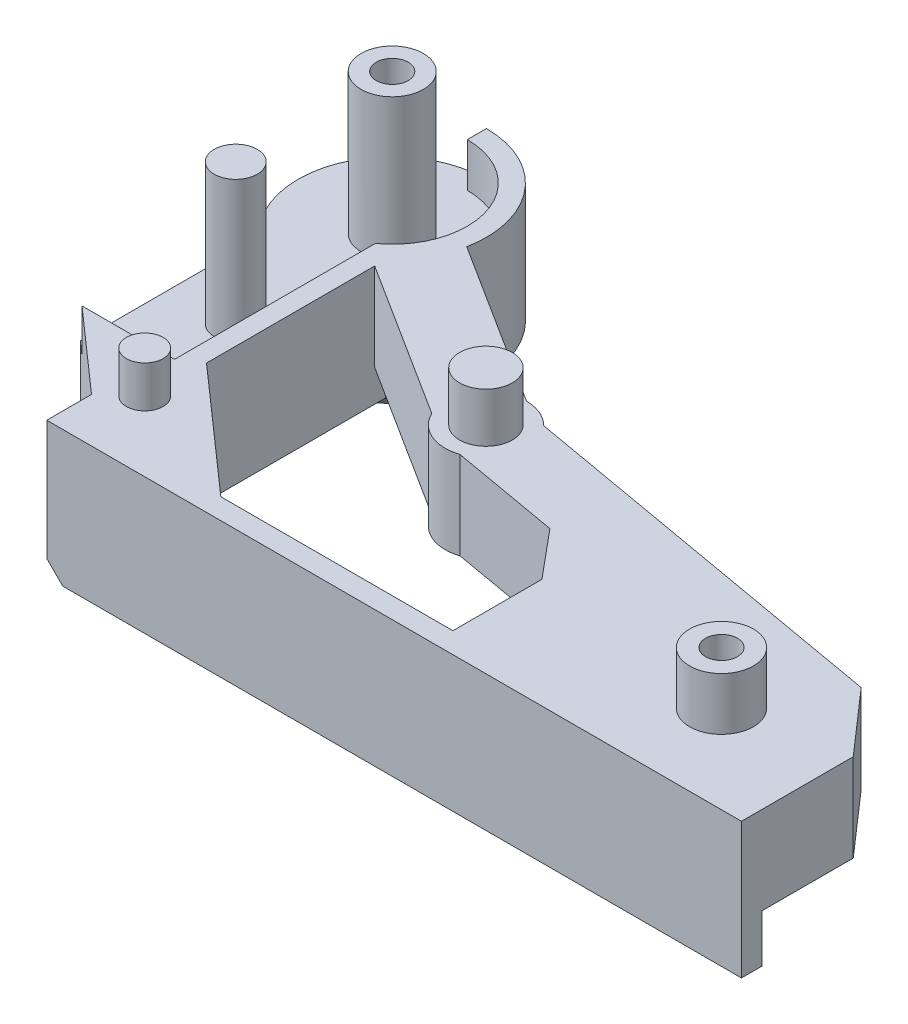
SolidWorks part; units mm, degrees
ref_plane "Front Plane" through (0, 0, 0) normal (0, 0, 1) x (1, 0, 0)
ref_plane "Top Plane" through (0, 0, 0) normal (0, 1, 0) x (1, 0, 0)
ref_plane "Right Plane" through (0, 0, 0) normal (1, 0, 0) x (0, 0, -1)
sketch "Sketch1" plane through (0, 0, 0) normal (0, 1, 0) x (1, 0, 0)
  line L0 (21.75, 0) -> (-21.75, 0)
  line L1 (-21.75, 0) -> (-21.75, 1.3)
  line L2 (-21.75, 1.3) -> (21.75, 1.3)
  line L3 (21.75, 1.3) -> (21.75, 0)
  line L4 (21.75, 0) -> (21.75, 7)
  line L5 (21.75, 7) -> (18.25, 11)
  line L6 (18.25, 11) -> (-7.25, 15.5)
  line L7 (-7.9973, 11.2654) -> (-0.119, 9.8751)
  line L8 (-7.25, 15.5) -> (-7.9973, 11.2654)
  line L9 (-0.119, 9.8751) -> (2.381, 6.8751)
  line L10 (2.381, 6.8751) -> (2.381, 1.3)
  line L11 (-8.9018, 11.6845) -> (-6.5982, 15.3155)
  line L12 (-6.5982, 15.3155) -> (-21.7974, 24.9583)
  line L13 (-21.7974, 24.9583) -> (-24.101, 21.3274)
  line L14 (-24.101, 21.3274) -> (-8.9018, 11.6845)
  line L15 (-7.75, 13.5) -> (-23.8, 23.6826) construction
  line L16 (-21.75, 0) -> (-21.75, 2.8)
  line L17 (-21.75, 2.8) -> (-27.75, 8.1)
  line L18 (-27.75, 8.1) -> (-27.75, 19.3)
  line L19 (-27.75, 19.3) -> (-19.85, 19.3)
  line L20 (-19.85, 19.3) -> (-19.85, 8.1)
  line L21 (-19.85, 8.1) -> (-12.1519, 1.3)
  circle A0 centre (-7.75, 13.5) radius 1.65
  circle A1 centre (-7.75, 13.5) radius 2.55
  circle A2 centre (-23.8, 23.6826) radius 5.9
  point P4 (0, 0)
  dimension "D15" = 3.3
  dimension "D16" = 5.1
  dimension "D25" = 11.8
  dimension "D1" = 1.3
  dimension "D2" = 43.5
  dimension "D3" = 0
  dimension "D4" = 7
  dimension "D5" = 4
  dimension "D6" = 3.5
  dimension "D7" = 29
  dimension "D8" = 15.5
  dimension "D9" = 4.3
  dimension "D10" = 8
  dimension "D11" = 3
  dimension "D12" = 2.5
  dimension "D13" = 29.5
  dimension "D14" = 13.5
  dimension "D17" = 4.3
  dimension "D18" = 18
  dimension "D19" = 2.8
  dimension "D20" = 6
  dimension "D21" = 5.3
  dimension "D22" = 11.2
  dimension "D23" = 7.9
  dimension "D24" = 11.2
extrude "Boss-Extrude1" add sketch "Sketch1" along normal blind 5.5
sketch "Sketch2" plane through (0, 5.5, 0) normal (0, 1, 0) x (1, 0, 0)
  circle A0 centre (-7.75, 13.5) radius 1.65
  dimension "D1" = 3.3
extrude "Cut-Extrude1" cut sketch "Sketch2" against normal blind 5.5
sketch "Sketch3" plane through (0, 5.5, 0) normal (0, 1, 0) x (1, 0, 0)
  line L0 (-19.85, 8.1) -> (-19.85, 19.3)
  line L1 (-27.75, 8.1) -> (-27.75, 19.3)
  line L2 (-27.75, 8.1) -> (-21.75, 2.8)
  line L3 (-21.75, 2.8) -> (-21.75, 0)
  line L4 (-21.75, 0) -> (21.75, 0)
  line L5 (21.75, 0) -> (21.75, 1.3)
  line L6 (21.75, 0) -> (21.75, 7) construction
  line L7 (21.75, 1.3) -> (-12.1519, 1.3)
  line L8 (-12.1519, 1.3) -> (-19.85, 8.1)
  circle A0 centre (-23.8, 23.6826) radius 5.9
  line M8 (2.381, 1.3) -> (-12.1519, 1.3)
  line M9 (-12.1519, 1.3) -> (-19.85, 8.1)
  line M10 (-19.85, 8.1) -> (-19.85, 18.6304)
  arc M14 (-18.0088, 22.5547) -> (-27.75, 19.3) centre (-23.8, 23.6826) ccw
  line M15 (-27.75, 19.3) -> (-27.75, 8.1)
  line M16 (-27.75, 8.1) -> (-21.75, 2.8)
  line M17 (-21.75, 2.8) -> (-21.75, 0)
  line M18 (-21.75, 0) -> (21.75, 0)
  line M19 (21.75, 0) -> (21.75, 7)
  dimension "D1" = 11.8
extrude "Boss-Extrude2" add sketch "Sketch3" along normal blind 3 contours A0 M14 | A0 L7 L0 M15 M16 M17 M18 M19 M8 M9 M10
sketch "Sketch4" plane through (0, 0, 0) normal (0, -1, 0) x (1, 0, 0)
  line L0 (-23.8, -29.5826) -> (-23.8, -7.3)
  line L1 (-23.8, -7.3) -> (-26.8443, -7.3)
  line L2 (-21.75, -2.8) -> (-27.75, -8.1) construction
  line L3 (-26.8443, -7.3) -> (-27.75, -8.1)
  line L4 (-27.75, -8.1) -> (-27.75, -19.3)
  arc A0 (-27.75, -19.3) -> (-18.0088, -22.5547) centre (-23.8, -23.6826) ccw construction
  circle A1 centre (-23.8, -23.6826) radius 5.9
  line M18 (-21.75, -2.8) -> (-27.75, -8.1)
  line M19 (-27.75, -8.1) -> (-27.75, -19.3)
  arc M20 (-27.75, -19.3) -> (-18.0088, -22.5547) centre (-23.8, -23.6826) ccw
  dimension "D2" = 11.8
  dimension "D1" = 0.8
extrude "Cut-Extrude2" cut sketch "Sketch4" against normal offset from surface (2.75 mm away) 5.75 contours L0 A1 M20 | A1 L0 L1 M18 M19
sketch "Sketch5" plane through (0, 0, 0) normal (0, -1, 0) x (1, 0, 0)
  line L0 (21.75, 0) -> (-21.75, 0) construction
  circle A0 centre (-23.8, -23.6826) radius 1.95
  circle A1 centre (-23.8, -13.8826) radius 1.35
  circle A2 centre (-20, -4.3826) radius 1.15
  circle A3 centre (15.0006, -5.5) radius 2
  dimension "D1" = 3.9
  dimension "D3" = 2.7
  dimension "D7" = 2.3
  dimension "D8" = 4
  dimension "D2" = 0
  dimension "D4" = 3.8
  dimension "D5" = 9.5
  dimension "D6" = 9.8
  dimension "D9" = 38.8006
  dimension "D10" = 5.5
extrude "Cut-Extrude3" cut sketch "Sketch5" against normal offset from surface (4.3 mm away) 1.2 up to face at (-1.7017, 5.5, -11.7406)
sketch "Sketch7" plane through (0, 4.3, 0) normal (0, -1, 0) x (1, 0, 0)
  circle A0 centre (-23.8, -13.8826) radius 1.35
  circle A1 centre (-23.8, -23.6826) radius 1.95
  dimension "D1" = 3.9
  dimension "D2" = 2.7
extrude "Cut-Extrude4" cut sketch "Sketch7" against normal offset from surface (3 mm away) 1.2 contours A1 | A0 up to face at (-11.928, 8.5, -7.8314)
chamfer "Chamfer1" distance 1 angle 45 5 edges at (-21.75, 8.5, -1.4) (-24.75, 8.5, -5.45) (-27.75, 8.5, -13.7) (-19.85, 8.5, -13.7) (-23.8, 8.5, -29.5826)
sketch "Sketch8" plane through (0, 0, 0) normal (0, -1, 0) x (1, 0, 0)
  line L0 (-23.8, -7.3) -> (-21.05, -7.3)
  line L1 (-21.05, -7.3) -> (-21.05, -19.8711)
  line L2 (-19.85, -18.6304) -> (-19.85, -8.1) construction
  line L3 (-23.8, -7.3) -> (-23.8, -18.9826)
  circle A0 centre (-23.8, -23.6826) radius 4.7
  arc A1 (-23.8, -29.5826) -> (-18.0088, -22.5547) centre (-23.8, -23.6826) ccw construction
  line M13 (-23.8, -15.2326) -> (-23.8, -21.7326)
  arc M14 (-23.8, -21.7326) -> (-23.8, -25.6326) centre (-23.8, -23.6826) cw
  line M15 (-23.8, -25.6326) -> (-23.8, -29.5826)
  line M26 (-23.8, -7.3) -> (-23.8, -12.5326)
  arc M27 (-23.8, -12.5326) -> (-23.8, -15.2326) centre (-23.8, -13.8826) cw
  dimension "D1" = 1.2
  dimension "D2" = 1.2
extrude "Cut-Extrude5" cut sketch "Sketch8" against normal up to surface (2.75 mm away) contours A0 L1 L0 M26 M27 M13 | A0 M15 M13 M14 up to face at (-25.7752, 2.75, -16.4522)
mirror "Mirror1" about plane through (0, 0, 0) normal (0, 1, 0) of bodies 107
delete or keep bodies "-1" type delete bodies bodies 107
sketch "Sketch9" plane through (0, -7.3, 0) normal (0, 1, 0) x (1, 0, 0)
  circle A0 centre (-23.8, 23.6826) radius 1.95
  dimension "D1" = 3.9
extrude "Boss-Extrude3" add sketch "Sketch9" along normal offset from surface (13.35 mm away) 8.8
sketch "Sketch10" plane through (0, 6.05, 0) normal (0, 1, 0) x (1, 0, 0)
  circle A0 centre (-23.8, 23.6826) radius 1
  dimension "D1" = 2
extrude "Cut-Extrude6" cut sketch "Sketch10" against normal up to surface (8.8 mm away)
sketch "Sketch11" plane through (0, -7.3, 0) normal (0, 1, 0) x (1, 0, 0)
  circle A0 centre (-23.8, 13.8826) radius 1.35
  dimension "D1" = 2.7
extrude "Boss-Extrude4" add sketch "Sketch11" along normal offset from surface (13.35 mm away) 8.8
sketch "Sketch12" plane through (0, -4.3, 0) normal (0, 1, 0) x (1, 0, 0)
  circle A0 centre (-20, 4.3826) radius 1.15
  dimension "D1" = 2.3
extrude "Boss-Extrude5" add sketch "Sketch12" along normal offset from surface (6.9 mm away) 2.6
sketch "Sketch13" plane through (0, -4.3, 0) normal (0, 1, 0) x (1, 0, 0)
  circle A0 centre (15.0006, 5.5) radius 2
  dimension "D1" = 4
extrude "Boss-Extrude6" add sketch "Sketch13" along normal offset from surface (7.6 mm away) 3.3
sketch "Sketch14" plane through (0, 3.3, 0) normal (0, 1, 0) x (1, 0, 0)
  circle A0 centre (15.0006, 5.5) radius 1
  dimension "D1" = 2
extrude "Cut-Extrude7" cut sketch "Sketch14" against normal up to surface (3.3 mm away)
sketch "Sketch15" plane through (0, 0, 0) normal (0, 1, 0) x (1, 0, 0)
  circle A0 centre (-7.75, 13.5) radius 1.65
  dimension "D1" = 3.3
extrude "Boss-Extrude7" add sketch "Sketch15" against normal blind 1.2 and the other way blind 3.1
sketch "Sketch16" plane through (0, -1.2, 0) normal (0, -1, 0) x (1, 0, 0)
  circle A0 centre (-7.75, -13.5) radius 1
  dimension "D1" = 2
extrude "Cut-Extrude8" cut sketch "Sketch16" against normal offset from surface (3.1 mm away) 1.2 up to face at (-7.75, 3.1, -11.85)
